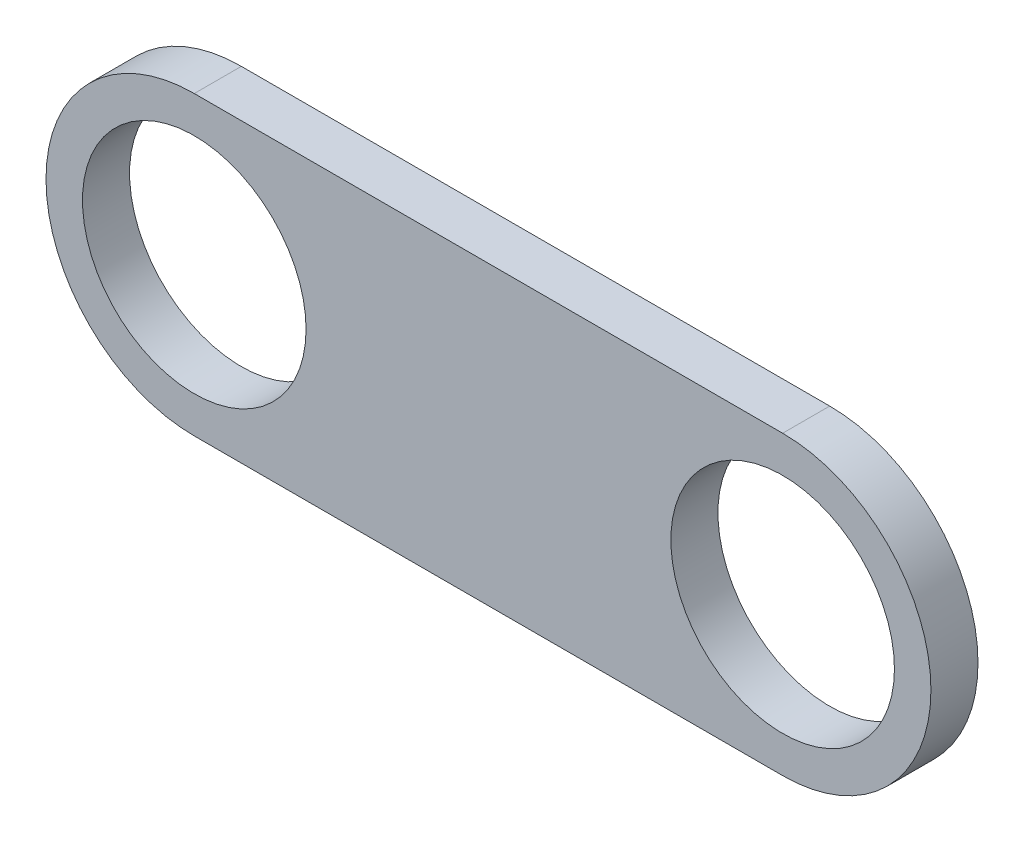
SolidWorks part; units mm, degrees
material "PLA"
ref_plane "Front Plane" through (0, 0, 0) normal (0, 0, 1) x (1, 0, 0)
ref_plane "Top Plane" through (0, 0, 0) normal (0, 1, 0) x (1, 0, 0)
ref_plane "Right Plane" through (0, 0, 0) normal (1, 0, 0) x (0, 0, -1)
sketch "Sketch1" plane through (0, 0, 0) normal (0, 0, 1) x (1, 0, 0)
  line L0 (-80.8735, 0) -> (80.8735, 0) construction
  line L1 (0, 12.6) -> (50, 12.6)
  line L2 (0, -12.6) -> (50, -12.6)
  arc A0 (50, -12.6) -> (50, 12.6) centre (50, 0) ccw
  arc A1 (0, 12.6) -> (0, -12.6) centre (0, 0) ccw
  circle A2 centre (50, 0) radius 9.5
  circle A3 centre (0, 0) radius 9.5
  dimension "D1" = 25.2
  dimension "D2" = 25.2
  dimension "D3" = 50
  dimension "D4" = 19
  dimension "D5" = 19
extrude "Boss-Extrude1" add sketch "Sketch1" along normal blind 4
